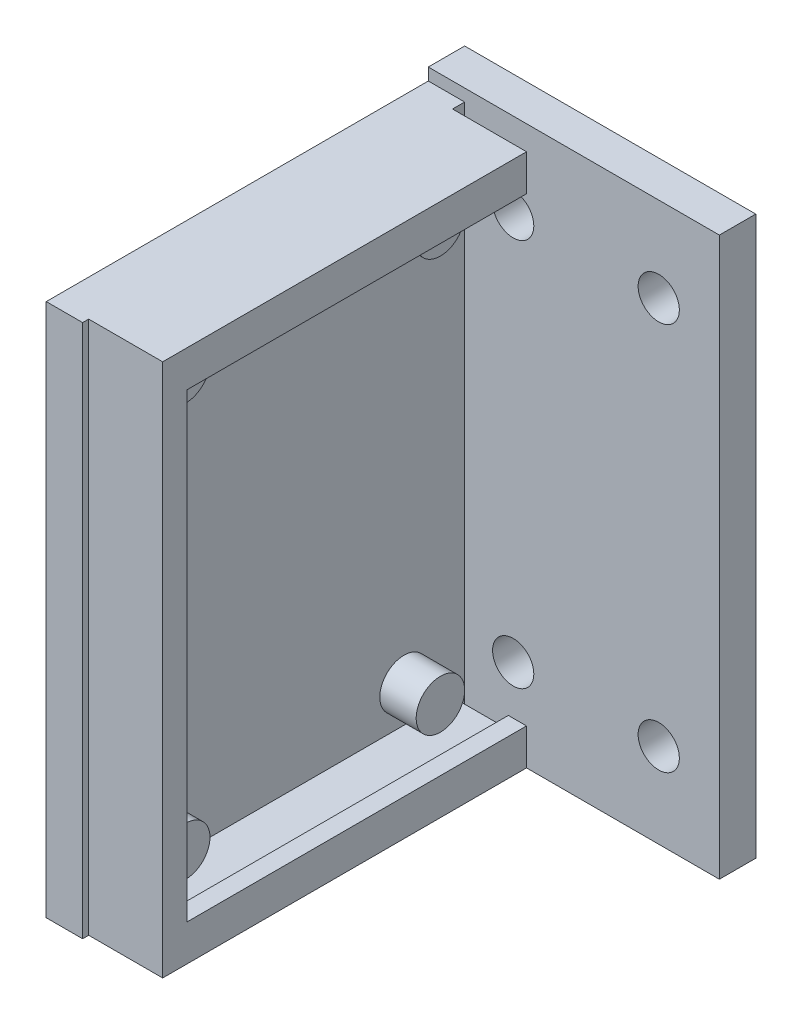
SolidWorks part; units mm, degrees
other "Camera Clip Bracket"
ref_plane "Front Plane" through (0, 0, 0) normal (0, 0, 1) x (1, 0, 0)
ref_plane "Top Plane" through (0, 0, 0) normal (0, 1, 0) x (1, 0, 0)
ref_plane "Right Plane" through (0, 0, 0) normal (1, 0, 0) x (0, 0, -1)
sketch3d "Mounting Foot Sketch datum points"
  point P0 (0, 0, 111.5)
  point P1 (10, 0, 111.5)
  point P2 (0, 10, 111.5)
ref_plane "Mounting Foot Sketch plane" through (0, 0, 111.5) normal (0, 0, 1) x (1, 0, 0)
sketch "Mounting Foot Sketch" plane through (0, 0, 111.5) normal (0, 0, 1) x (1, 0, 0)
  line L0 (178, -23) -> (202, -23)
  line L1 (202, -23) -> (202, 23)
  line L2 (202, 23) -> (178, 23)
  line L3 (178, 23) -> (178, -23)
extrude "Mounting Foot" add sketch "Mounting Foot Sketch" along normal blind 3 separate body
sketch3d "Back Plate Sketch datum points"
  point P0 (0, 0, 114.5)
  point P1 (10, 0, 114.5)
  point P2 (0, 10, 114.5)
ref_plane "Back Plate Sketch plane" through (0, 0, 114.5) normal (0, 0, 1) x (1, 0, 0)
sketch "Back Plate Sketch" plane through (0, 0, 114.5) normal (0, 0, 1) x (1, 0, 0)
  line L0 (178, -22) -> (181, -22)
  line L1 (181, -22) -> (181, 22)
  line L2 (181, 22) -> (178, 22)
  line L3 (178, 22) -> (178, -22)
extrude "Back Plate" add sketch "Back Plate Sketch" along normal blind 31.5
sketch3d "Clip Rail Sketch datum points"
  point P0 (0, 0, 115.5)
  point P1 (10, 0, 115.5)
  point P2 (0, 10, 115.5)
ref_plane "Clip Rail Sketch plane" through (0, 0, 115.5) normal (0, 0, 1) x (1, 0, 0)
sketch "Clip Rail Sketch" plane through (0, 0, 115.5) normal (0, 0, 1) x (1, 0, 0)
  line L0 (181, -22) -> (187.1, -22)
  line L1 (187.1, -22) -> (187.1, -19)
  line L2 (187.1, -19) -> (185.6, -19)
  line L3 (185.6, -19) -> (185.6, -20)
  line L4 (185.6, -20) -> (181, -20)
  line L5 (181, -20) -> (181, -22)
  line L6 (181, 20) -> (185.6, 20)
  line L7 (185.6, 20) -> (185.6, 19)
  line L8 (185.6, 19) -> (187.1, 19)
  line L9 (187.1, 19) -> (187.1, 22)
  line L10 (187.1, 22) -> (181, 22)
  line L11 (181, 22) -> (181, 20)
extrude "Clip Rails" add sketch "Clip Rail Sketch" along normal blind 30
sketch3d "Top Retaining Rail Sketch datum points"
  point P0 (0, 0, 143.5)
  point P1 (10, 0, 143.5)
  point P2 (0, 10, 143.5)
ref_plane "Top Retaining Rail Sketch plane" through (0, 0, 143.5) normal (0, 0, 1) x (1, 0, 0)
sketch "Top Retaining Rail Sketch" plane through (0, 0, 143.5) normal (0, 0, 1) x (1, 0, 0)
  line L0 (181, -20) -> (187.1, -20)
  line L1 (187.1, -20) -> (187.1, 20)
  line L2 (187.1, 20) -> (181, 20)
  line L3 (181, 20) -> (181, -20)
extrude "Top Retaining Rail" add sketch "Top Retaining Rail Sketch" along normal blind 2
sketch3d "PCB Support Sketch datum points"
  point P0 (181, 0, 0)
  point P1 (181, 10, 0)
  point P2 (181, 0, 10)
ref_plane "PCB Support Sketch plane" through (181, 0, 0) normal (1, 0, 0) x (0, 0, -1)
sketch "PCB Support Sketch" plane through (181, 0, 0) normal (1, 0, 0) x (0, 0, -1)
  circle A0 centre (-119.5, -17) radius 2
  circle A1 centre (-140.5, -17) radius 2
  circle A2 centre (-119.5, 17) radius 2
  circle A3 centre (-140.5, 17) radius 2
extrude "PCB Supports" add sketch "PCB Support Sketch" along normal blind 3
sketch3d "Mounting Holes Sketch datum points"
  point P0 (0, 0, 111.4)
  point P1 (10, 0, 111.4)
  point P2 (0, 10, 111.4)
ref_plane "Mounting Holes Sketch plane" through (0, 0, 111.4) normal (0, 0, 1) x (1, 0, 0)
sketch "Mounting Holes Sketch" plane through (0, 0, 111.4) normal (0, 0, 1) x (1, 0, 0)
  circle A0 centre (185, -16) radius 1.7
  circle A1 centre (185, 16) radius 1.7
  circle A2 centre (197, -16) radius 1.7
  circle A3 centre (197, 16) radius 1.7
extrude "Mounting Holes" cut sketch "Mounting Holes Sketch" along normal blind 3.2
